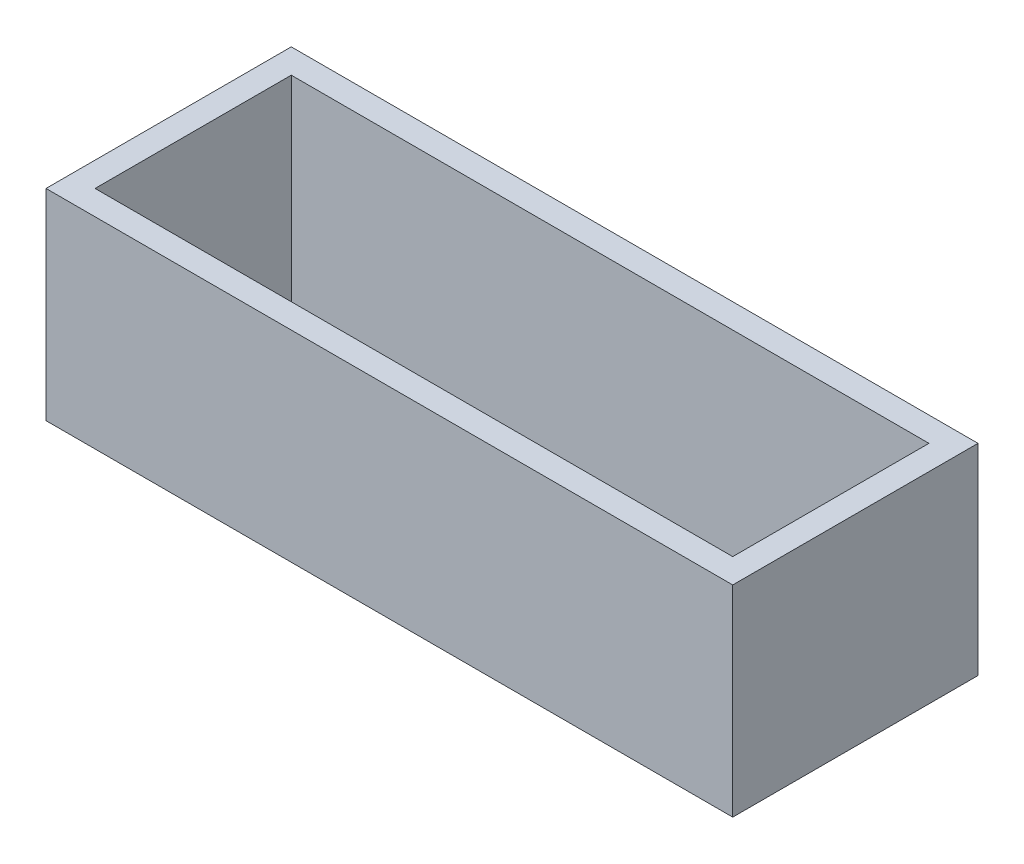
SolidWorks part; units mm, degrees
material "Polyurethane Foam Rigid"
ref_plane "Front Plane" through (0, 0, 0) normal (0, 0, 1) x (1, 0, 0)
ref_plane "Top Plane" through (0, 0, 0) normal (0, 1, 0) x (1, 0, 0)
ref_plane "Right Plane" through (0, 0, 0) normal (1, 0, 0) x (0, 0, -1)
sketch "Sketch1" plane through (0, 0, 0) normal (0, 1, 0) x (1, 0, 0)
  line L1 (-177.8, -63.5) -> (177.8, -63.5)
  line L2 (-177.8, -63.5) -> (-177.8, 63.5)
  line L3 (-177.8, 63.5) -> (177.8, 63.5)
  line L4 (177.8, -63.5) -> (177.8, 63.5)
  line L5 (-177.8, -63.5) -> (177.8, 63.5) construction
  line L6 (-177.8, 63.5) -> (177.8, -63.5) construction
  point P0 (0, 0)
  dimension "D1" = 127
  dimension "D2" = 355.6
extrude "Boss-Extrude1" add sketch "Sketch1" along normal blind 2.54
sketch "Sketch2" plane through (0, 2.54, 0) normal (0, 1, 0) x (1, 0, 0)
  line L1 (-165.1, -50.8) -> (165.1, -50.8)
  line L2 (-165.1, -50.8) -> (-165.1, 50.8)
  line L3 (-165.1, 50.8) -> (165.1, 50.8)
  line L4 (165.1, -50.8) -> (165.1, 50.8)
  line L5 (-165.1, -50.8) -> (165.1, 50.8) construction
  line L6 (-165.1, 50.8) -> (165.1, -50.8) construction
  line L7 (-177.8, -63.5) -> (177.8, -63.5)
  line L8 (-177.8, -63.5) -> (-177.8, 63.5)
  line L9 (-177.8, 63.5) -> (177.8, 63.5)
  line L10 (177.8, -63.5) -> (177.8, 63.5)
  line L11 (-177.8, -63.5) -> (177.8, 63.5) construction
  line L12 (-177.8, 63.5) -> (177.8, -63.5) construction
  point P0 (0, 0)
  point P5 (0, 0)
  dimension "D1" = 101.6
  dimension "D2" = 330.2
extrude "Boss-Extrude2" add sketch "Sketch2" along normal blind 101.6
